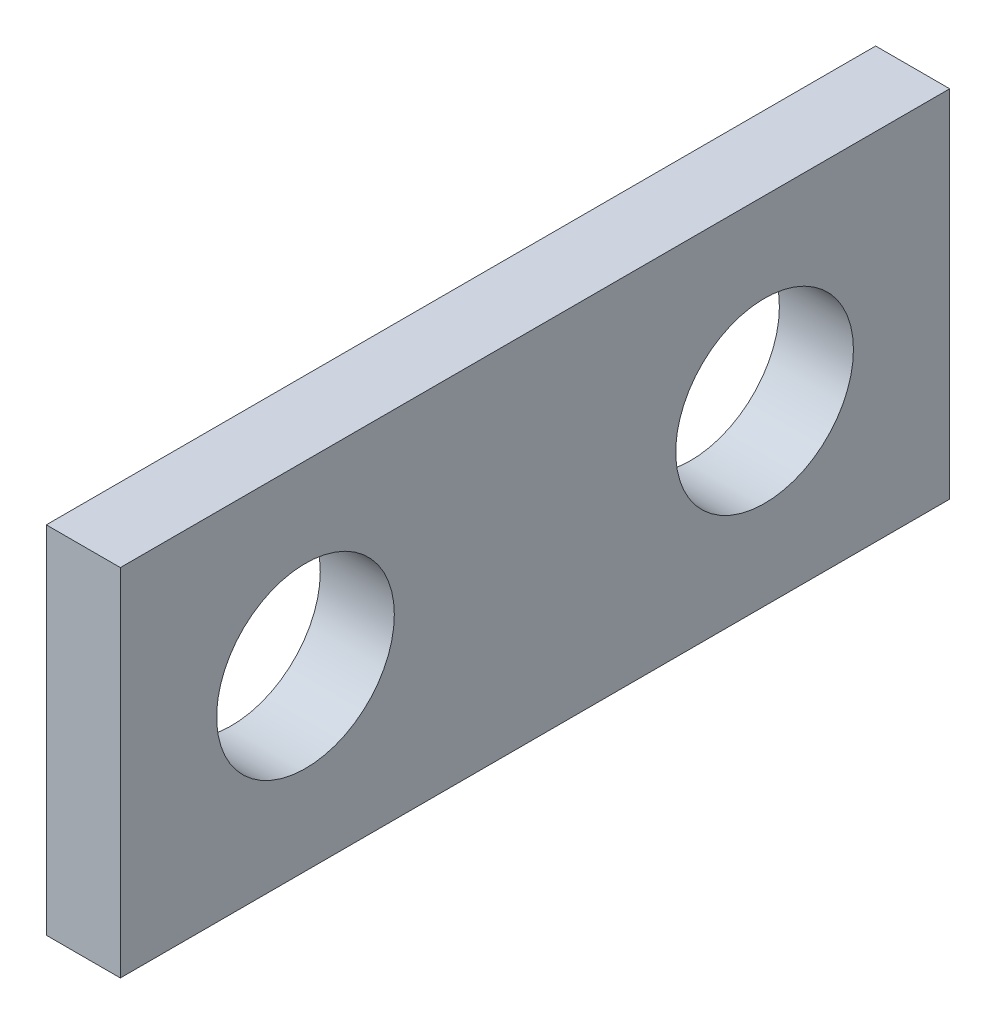
SolidWorks part; units mm, degrees
ref_plane "Front Plane" through (0, 0, 0) normal (0, 0, 1) x (1, 0, 0)
ref_plane "Top Plane" through (0, 0, 0) normal (0, 1, 0) x (1, 0, 0)
ref_plane "Right Plane" through (0, 0, 0) normal (1, 0, 0) x (0, 0, -1)
sketch "Sketch1" plane through (0, 0, 0) normal (1, 0, 0) x (0, 0, -1)
  line L0 (-3, 12) -> (-3, -12) construction
  line L1 (-28, -12) -> (28, -12)
  line L2 (-28, -12) -> (-28, 12)
  line L3 (-28, 12) -> (28, 12)
  line L4 (28, -12) -> (28, 12)
  line L5 (-28, -12) -> (28, 12) construction
  line L6 (-28, 12) -> (28, -12) construction
  line L7 (3, 12) -> (3, -12) construction
  line L8 (-28, 12) -> (-3, -12) construction
  line L9 (-28, -12) -> (-3, 12) construction
  line L10 (3, 12) -> (28, -12) construction
  line L11 (28, 12) -> (3, -12) construction
  circle A0 centre (-15.5, 0) radius 6
  circle A1 centre (15.5, 0) radius 6
  point P0 (0, 0)
  dimension "D3" = 12
  dimension "D1" = 56
  dimension "D2" = 25
  dimension "D4" = 24
extrude "Boss-Extrude1" add sketch "Sketch1" along normal blind 5
equation "\"CarriageWidth\"=56"
equation "\"D1@Sketch1\"=\"CarriageWidth\""
